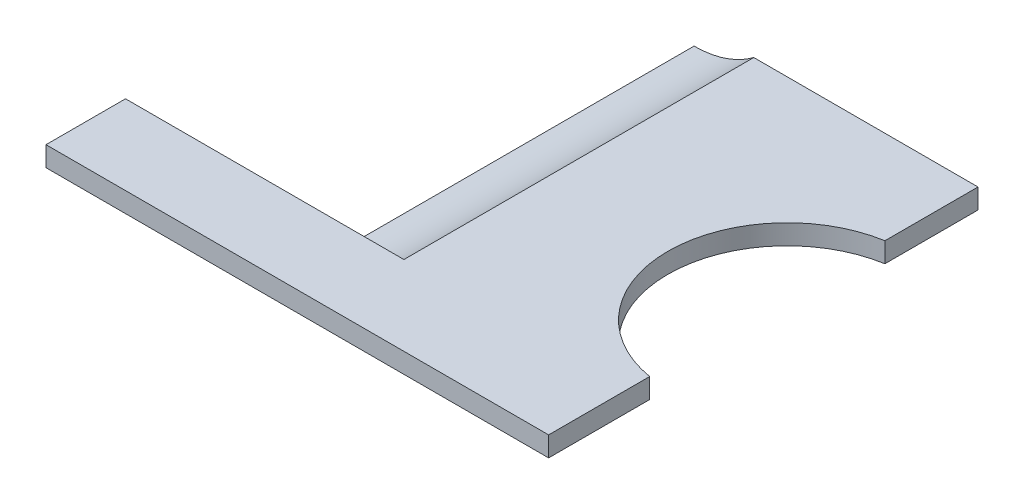
SolidWorks part; units mm, degrees
ref_plane "정면" through (0, 0, 0) normal (0, 0, 1) x (1, 0, 0)
ref_plane "윗면" through (0, 0, 0) normal (0, 1, 0) x (1, 0, 0)
ref_plane "우측면" through (0, 0, 0) normal (1, 0, 0) x (0, 0, -1)
sketch "스케치1" plane through (0, 0, 0) normal (0, 0, 1) x (1, 0, 0)
  line L0 (0, -2.5) -> (-5.5, -2.5)
  line L1 (-5.5, -2.5) -> (-5.5, -1.9979)
  line L2 (-5.5, -1.9979) -> (0.0924, -1.9979)
  line L3 (0.0924, -1.9979) -> (7.1424, -1.9979)
  line L4 (7.1424, -1.9979) -> (7.1424, -2.5)
  line L5 (7.1424, -2.5) -> (0, -2.5)
  circle A0 centre (0, 0) radius 2.5
  point P8 (0, 0)
  point P9 (0, 0)
  dimension "D4" = 5
  dimension "D1" = 0.5021
  dimension "D2" = 5.5
  dimension "D3" = 7.1424
  dimension "D6" = 5.5924
extrude "보스-돌출1" add sketch "스케치1" along normal blind 2 contours A0 L2 L1 L0 | L2 A0 L3 | A0 L5 L4 L3
sketch "스케치2" plane through (0, 0, 2) normal (0, 0, 1) x (1, 0, 0)
  line L3 (1.5028, -1.9979) -> (7.1424, -1.9979)
  line L4 (7.1424, -1.9979) -> (7.1424, -2.5)
  line L5 (7.1424, -2.5) -> (0, -2.5)
  arc A0 (0, -2.5) -> (1.5028, -1.9979) centre (0, 0) ccw
  point P8 (0, 0)
  dimension "D4" = 5
  dimension "D1" = 5.6395
  dimension "D3" = 7.1424
extrude "보스-돌출2" add sketch "스케치2" against normal blind 10.8
sketch "스케치4" plane through (0, -2.5, 0) normal (0, -1, 0) x (1, 0, 0)
  line L0 (7.1424, 2) -> (7.1424, -8.8) construction
  line L5 (0, 0) -> (-5.5, 0) construction
  circle A0 centre (7.6424, -3.5) radius 3
  point P11 (3.5412, -7)
  dimension "D3" = 6
  dimension "D1" = 3.5
  dimension "D4" = 0.5
extrude "컷-돌출2" cut sketch "스케치4" against normal blind 10
